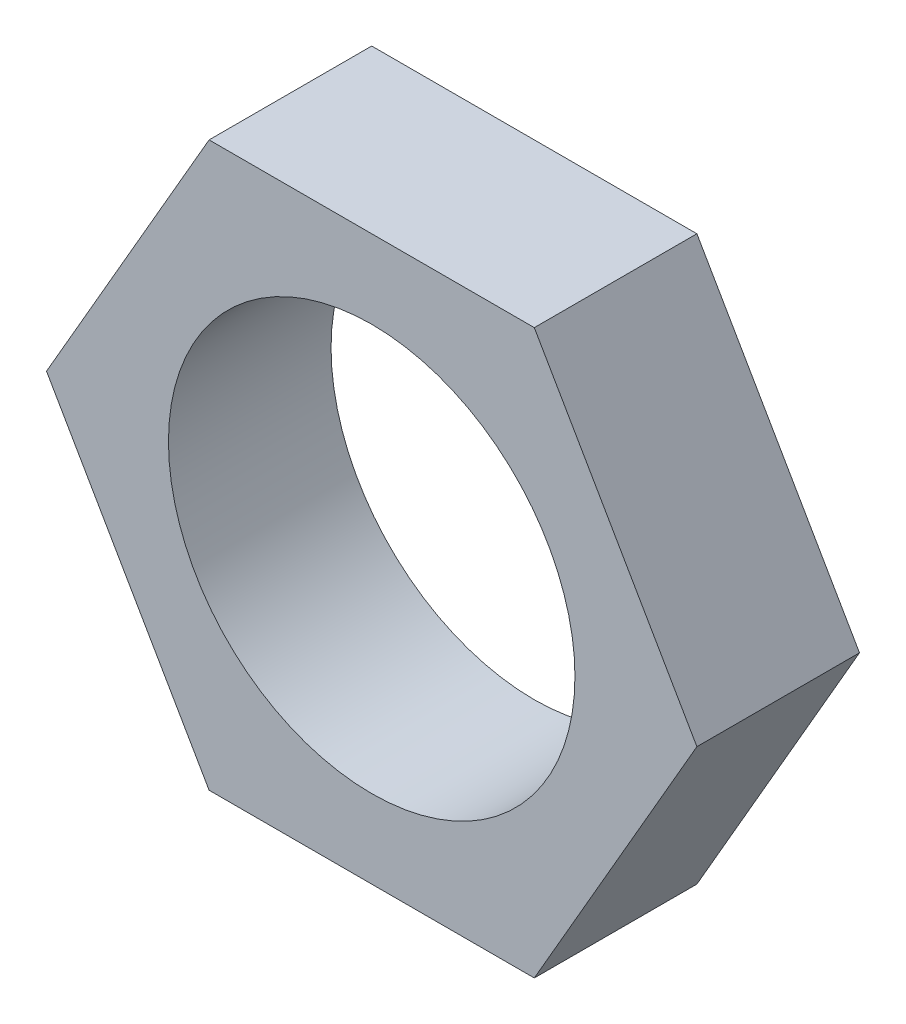
SolidWorks part; units mm, degrees
ref_plane "前视基准面" through (0, 0, 0) normal (0, 0, 1) x (1, 0, 0)
ref_plane "上视基准面" through (0, 0, 0) normal (0, 1, 0) x (1, 0, 0)
ref_plane "右视基准面" through (0, 0, 0) normal (1, 0, 0) x (0, 0, -1)
sketch "草图1" plane through (0, 0, 0) normal (0, 0, 1) x (1, 0, 0)
  line L1 (4, 0) -> (2, 3.4641)
  line L2 (2, 3.4641) -> (-2, 3.4641)
  line L3 (-2, 3.4641) -> (-4, 0)
  line L4 (-4, 0) -> (-2, -3.4641)
  line L5 (-2, -3.4641) -> (2, -3.4641)
  line L6 (2, -3.4641) -> (4, 0)
  circle A0 centre (0, 0) radius 3.4641 construction
  circle A1 centre (0, 0) radius 2.5
  dimension "D1" = 5
  dimension "D2" = 4
extrude "凸台-拉伸1" add sketch "草图1" along normal blind 2
cosmetic thread "装饰螺纹线1"
